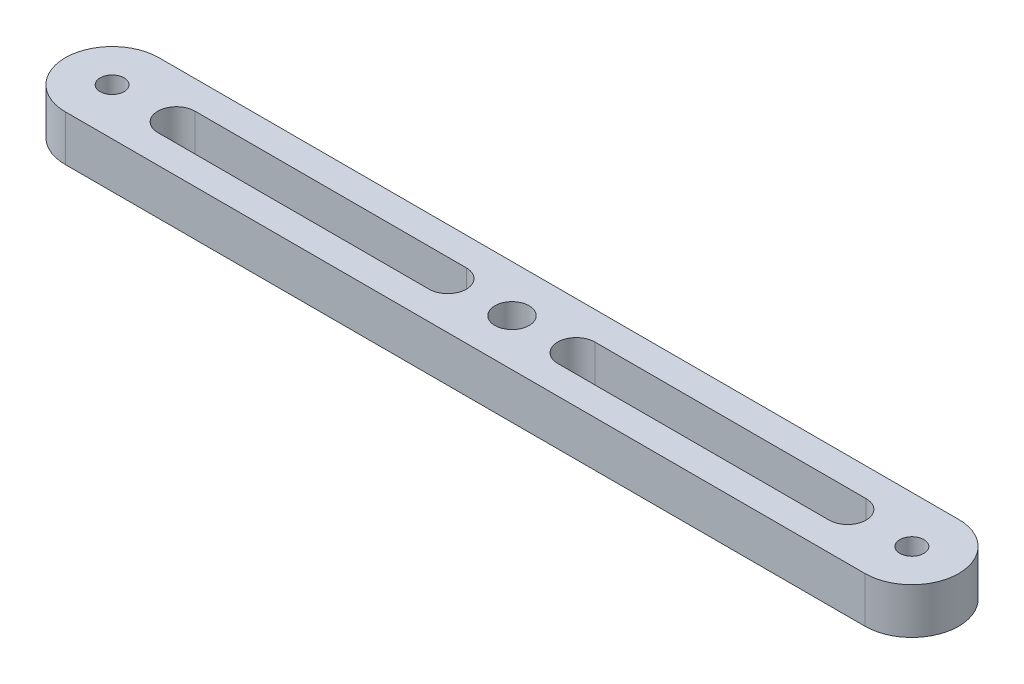
SolidWorks part; units mm, degrees
ref_plane "Front Plane" through (0, 0, 0) normal (0, 0, 1) x (1, 0, 0)
ref_plane "Top Plane" through (0, 0, 0) normal (0, 1, 0) x (1, 0, 0)
ref_plane "Right Plane" through (0, 0, 0) normal (1, 0, 0) x (0, 0, -1)
sketch "Sketch1" plane through (0, 0, 0) normal (0, 1, 0) x (1, 0, 0)
  line L0 (35, 0) -> (-35, 0) construction
  line L1 (35, -4.1) -> (-35, -4.1)
  line L2 (35, 4.1) -> (-35, 4.1)
  arc A0 (35, -4.1) -> (35, 4.1) centre (35, 0) ccw
  arc A1 (-35, 4.1) -> (-35, -4.1) centre (-35, 0) ccw
  point P2 (0, 0)
  dimension "D1" = 70
  dimension "D2" = 8.2
extrude "Boss-Extrude1" add sketch "Sketch1" against normal blind 4
sketch "Sketch2" plane through (0, 0, 0) normal (0, 1, 0) x (1, 0, 0)
  circle A0 centre (0, 0) radius 1.5
  dimension "D1" = 3
extrude "Cut-Extrude1" cut sketch "Sketch2" against normal up to surface (4 mm away) up to face at (0, -4, 0)
sketch "Sketch6" plane through (0, 0, 0) normal (0, 1, 0) x (1, 0, 0)
  circle A0 centre (-35, 0) radius 1.05
  arc A2 (-35, 4.1) -> (-35, -4.1) centre (-35, 0) ccw construction
  dimension "D1" = 2.1
extrude "Cut-Extrude2" cut sketch "Sketch6" against normal up to surface (4 mm away) up to face at (0, -4, 1.5)
sketch "Sketch7" plane through (0, 0, 0) normal (0, 1, 0) x (1, 0, 0)
  line L0 (-29.375, 0) -> (-5.625, 0) construction
  line L1 (-29.375, 1.625) -> (-5.625, 1.625)
  line L2 (-29.375, -1.625) -> (-5.625, -1.625)
  arc A0 (-29.375, 1.625) -> (-29.375, -1.625) centre (-29.375, 0) ccw
  arc A1 (-5.625, -1.625) -> (-5.625, 1.625) centre (-5.625, 0) ccw
  circle A2 centre (0, 0) radius 1.5 construction
  circle A3 centre (-35, 0) radius 1.05 construction
  point P3 (-17.5, 0)
  point P10 (-4, 0)
  point P11 (-31, 0)
  dimension "D1" = 4
  dimension "D2" = 4
  dimension "D3" = 3.25
  dimension "D4" = 29.375
  dimension "D5" = 23.75
extrude "Cut-Extrude3" cut sketch "Sketch7" against normal through all
mirror "Mirror1" about plane through (0, 0, 0) normal (1, 0, 0) of "Cut-Extrude3", "Cut-Extrude2"
